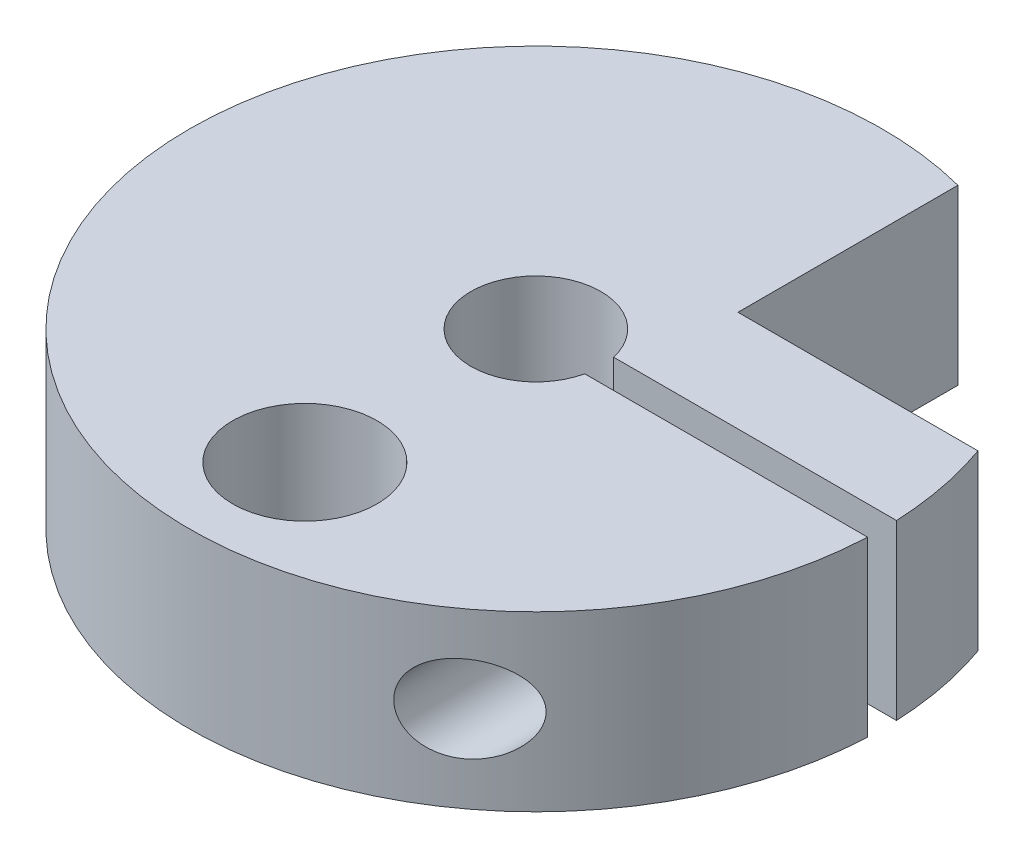
SolidWorks part; units mm, degrees
ref_plane "Front Plane" through (0, 0, 0) normal (0, 0, 1) x (1, 0, 0)
ref_plane "Top Plane" through (0, 0, 0) normal (0, 1, 0) x (1, 0, 0)
ref_plane "Right Plane" through (0, 0, 0) normal (1, 0, 0) x (0, 0, -1)
sketch "Sketch1" plane through (0, 0, 0) normal (0, 1, 0) x (1, 0, 0)
  line L1 (2.1937, 0.5) -> (11.9896, 0.5)
  line L2 (2.1937, -0.5) -> (11.9896, -0.5)
  line L3 (3, 11.619) -> (3, 4)
  line L4 (3, 4) -> (11.3137, 4)
  arc A0 (3, 11.619) -> (11.9896, -0.5) centre (0, 0) ccw
  arc A1 (2.1937, 0.5) -> (2.1937, -0.5) centre (0, 0) ccw
  circle A2 centre (0, -8) radius 2.5
  arc A3 (11.9896, 0.5) -> (11.3137, 4) centre (0, 0) ccw
  point P7 (0, 0)
  point P8 (0, 0)
  point P9 (0, 0)
  point P15 (0, 0)
  point P17 (0, 0)
  dimension "D1" = 24
  dimension "D2" = 5
  dimension "D3" = 4.5
  dimension "D4" = 8
  dimension "D5" = 3
  dimension "D6" = 4
  dimension "D7" = 1
  dimension "D8" = 0.5
extrude "Boss-Extrude1" add sketch "Sketch1" along normal blind 6
sketch "Sketch3" plane through (0, 0, -4) normal (0, 0, -1) x (-1, 0, 0)
  line L0 (-11.3137, 0) -> (-3, 0) construction
  line L1 (-3, 6) -> (-3, 0) construction
  circle A0 centre (-7.16, 3) radius 1.5
  dimension "D2" = 3
  dimension "D1" = 3
  dimension "D3" = 4.16
extrude "Cut-Extrude2" cut sketch "Sketch3" against normal blind 16
